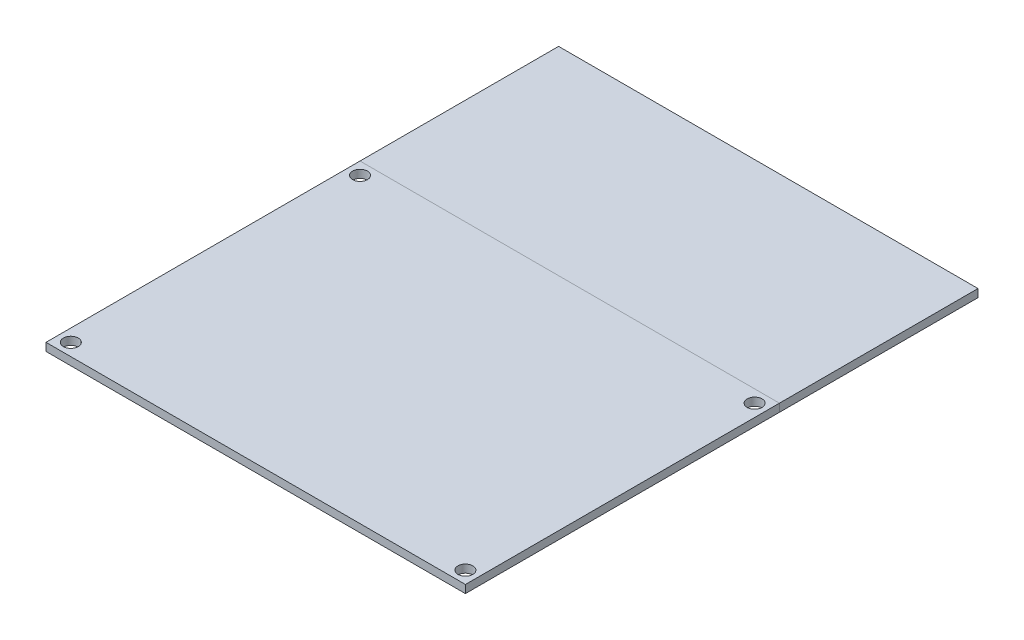
SolidWorks part; units mm, degrees
ref_plane "Front Plane" through (0, 0, 0) normal (0, 0, 1) x (1, 0, 0)
ref_plane "Top Plane" through (0, 0, 0) normal (0, 1, 0) x (1, 0, 0)
ref_plane "Right Plane" through (0, 0, 0) normal (1, 0, 0) x (0, 0, -1)
sketch "Sketch1" plane through (0, 0, 0) normal (0, 1, 0) x (1, 0, 0)
  line L0 (-55, 0) -> (55, 0) construction
  line L1 (-42.24, -31.625) -> (42.24, -31.625)
  line L2 (-42.24, -31.625) -> (-42.24, 31.625)
  line L3 (-42.24, 31.625) -> (42.24, 31.625)
  line L4 (42.24, -31.625) -> (42.24, 31.625)
  line L5 (-42.24, -31.625) -> (42.24, 31.625) construction
  line L6 (-42.24, 31.625) -> (42.24, -31.625) construction
  line L7 (0, -55) -> (0, 55) construction
  circle A0 centre (-39.74, 29.125) radius 1.5
  circle A1 centre (-39.74, -29.125) radius 1.5
  circle A2 centre (39.74, -29.125) radius 1.5
  circle A3 centre (39.74, 29.125) radius 1.5
  point P0 (0, 0)
  dimension "D3" = 3
  dimension "D1" = 63.25
  dimension "D2" = 84.48
  dimension "D4" = 2.5
  dimension "D5" = 2.5
extrude "Boss-Extrude1" add sketch "Sketch1" along normal blind 1.6
sketch "Sketch2" plane through (0, 0, 0) normal (0, 1, 0) x (1, 0, 0)
  line L1 (-42.24, 31.625) -> (42.24, 31.625)
  line L2 (-42.24, 31.625) -> (-42.24, 71.625)
  line L3 (-42.24, 71.625) -> (42.24, 71.625)
  line L4 (42.24, 31.625) -> (42.24, 71.625)
  dimension "D1" = 84.48
  dimension "D2" = 40
extrude "Boss-Extrude2" add sketch "Sketch2" along normal blind 1.6 separate body
